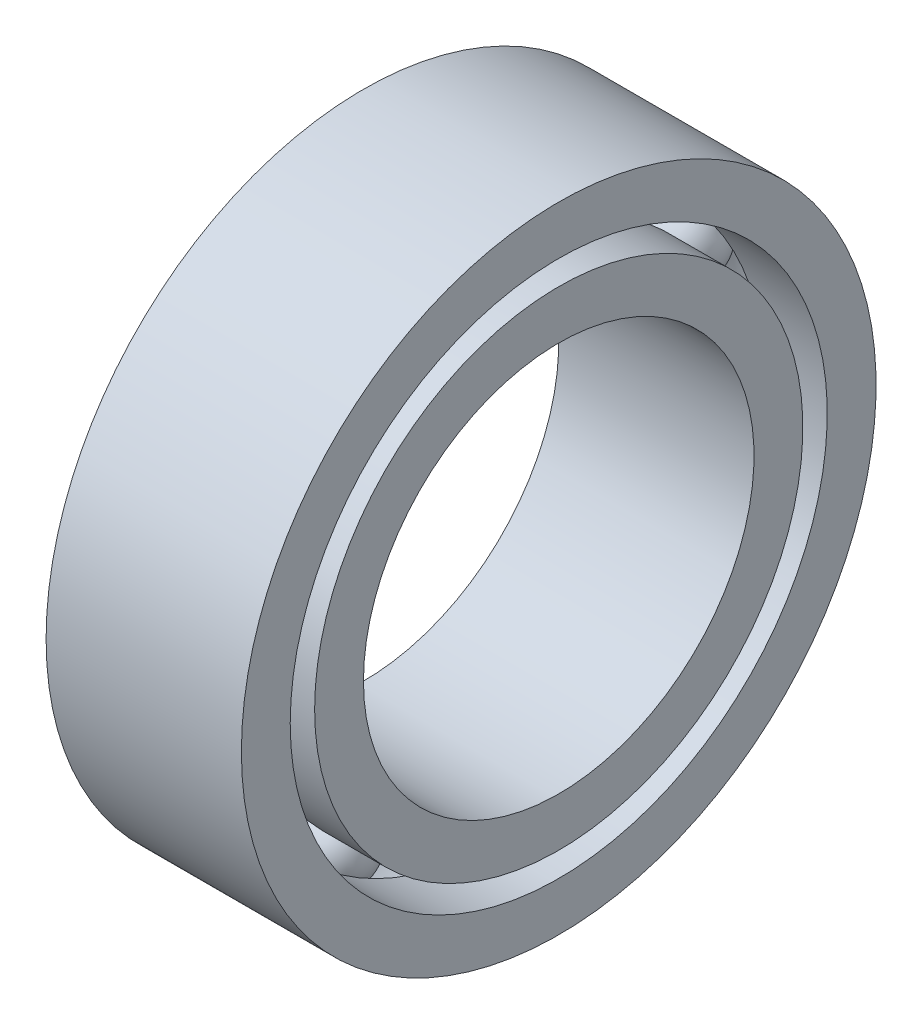
SolidWorks part; units mm, degrees
material "Cast Alloy Steel"
ref_plane "Front" through (0, 0, 0) normal (0, 0, 1) x (1, 0, 0)
ref_plane "Top" through (0, 0, 0) normal (0, 1, 0) x (1, 0, 0)
ref_plane "Right" through (0, 0, 0) normal (1, 0, 0) x (0, 0, -1)
sketch "Sketch2" plane through (0, 0, 0) normal (0, 0, 1) x (1, 0, 0)
  line L0 (0.003, 6.5) -> (2.003, 6.5)
  line L1 (2.003, 6.5) -> (2.003, 5.5)
  line L2 (2.003, 5.5) -> (0.7101, 5.5)
  line L3 (-1.997, 5.5) -> (-1.997, 6.5)
  line L4 (-1.997, 6.5) -> (0.003, 6.5)
  line L5 (0, 0) -> (2.8587, 0) construction
  line L6 (0.7101, 5) -> (2.003, 5)
  line L7 (2.003, 5) -> (2.003, 4)
  line L8 (2.003, 4) -> (0.003, 4)
  line L9 (0.003, 4) -> (-1.997, 4)
  line L10 (-1.997, 4) -> (-1.997, 5)
  line L11 (-1.997, 5) -> (-0.7041, 5)
  line L12 (0.003, 4) -> (0, 0) construction
  line L15 (-0.7041, 5.5) -> (-1.997, 5.5)
  arc A0 (0.7101, 5.5) -> (-0.7041, 5.5) centre (0.003, 5.25) ccw
  arc A1 (-0.7041, 5) -> (0.7101, 5) centre (0.003, 5.25) ccw
  point P17 (0.003, 5.25)
  dimension "D9" = 1.5
  dimension "D1" = 4
  dimension "D2" = 2
  dimension "D3" = 2
  dimension "D4" = 2
  dimension "D5" = 1
  dimension "D6" = 1
  dimension "D7" = 4
  dimension "D8" = 6.5
revolve "Revolve3" add sketch "Sketch2" angle 360 about L5
sketch "Sketch4" plane through (0, 0, 0) normal (0, 0, 1) x (1, 0, 0)
  line L0 (-0.747, 5.25) -> (0.753, 5.25)
  arc A0 (0.753, 5.25) -> (-0.747, 5.25) centre (0.003, 5.25) ccw
revolve "Revolve4" add sketch "Sketch4" angle 360 about L0
pattern_circular "CirPattern6" count 12 over 360 about axis through (0, 0, 0) along (1, 0, 0) of bodies 117
